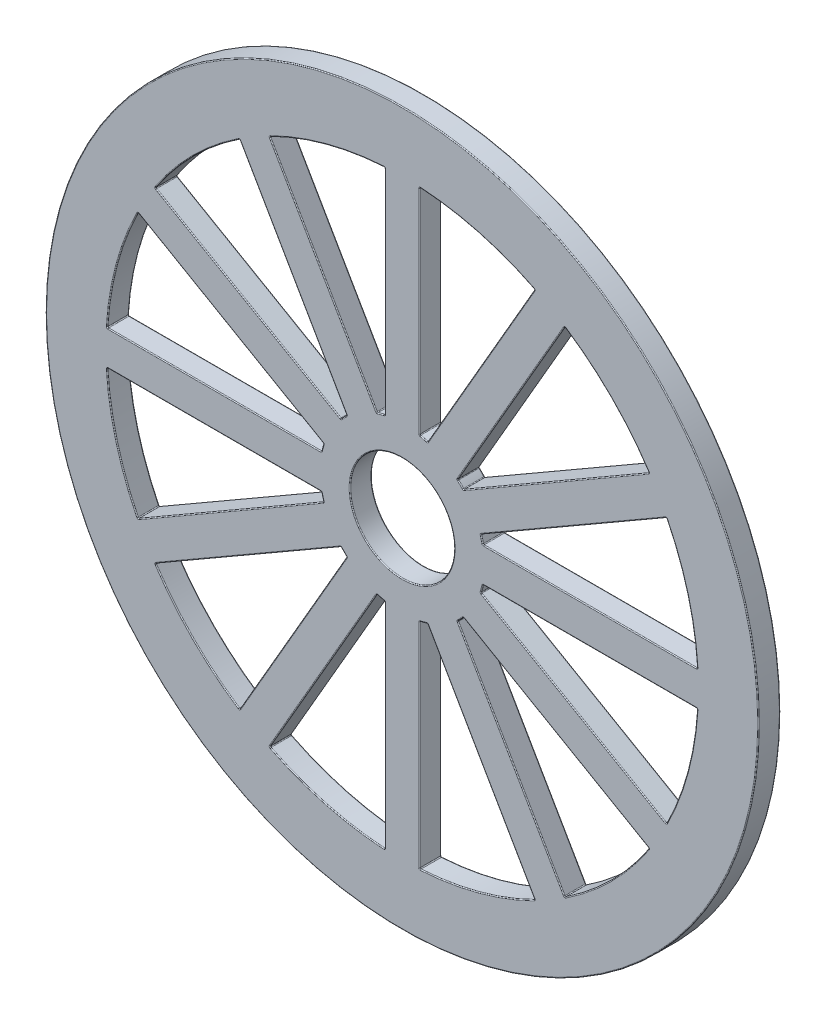
SolidWorks part; units mm, degrees
ref_plane "Plano frontal" through (0, 0, 0) normal (0, 0, 1) x (1, 0, 0)
ref_plane "Plano superior" through (0, 0, 0) normal (0, 1, 0) x (1, 0, 0)
ref_plane "Plano direito" through (0, 0, 0) normal (1, 0, 0) x (0, 0, -1)
sketch "Esboço1" plane through (0, 0, 0) normal (0, 0, 1) x (1, 0, 0)
  line L0 (-28.3848, 23.7524) -> (-28.3848, 48.4653)
  line L1 (-30.3848, 20.4653) -> (-30.3848, 48.4653) construction
  line L2 (-32.3848, 20.4653) -> (-32.3848, 48.4653) construction
  line L3 (-32.3848, 23.7524) -> (-32.3848, 48.4653)
  line L4 (-39.4276, 17.3768) -> (-60.8296, 29.7333)
  line L5 (-39.6718, 16.4653) -> (-64.3848, 16.4653)
  line L11 (-23.3419, 8.0897) -> (-1.9399, -4.2667)
  line L12 (-24.0092, 7.4224) -> (-11.6527, -13.9796)
  line L13 (-27.4733, 5.4224) -> (-15.1168, -15.9796)
  line L14 (-28.3848, 5.1782) -> (-28.3848, -19.5347)
  line L15 (-32.3848, 5.1782) -> (-32.3848, -19.5347)
  line L16 (-33.2963, 5.4224) -> (-45.6527, -15.9796)
  line L17 (-36.7604, 7.4224) -> (-49.1168, -13.9796)
  line L18 (-37.4276, 8.0897) -> (-58.8296, -4.2667)
  line L19 (-39.4276, 11.5538) -> (-60.8296, -0.8026)
  line L20 (-39.6718, 12.4653) -> (-64.3848, 12.4653)
  line L23 (-37.4276, 20.8409) -> (-58.8296, 33.1974)
  line L24 (-36.7604, 21.5082) -> (-49.1168, 42.9102)
  line L25 (-33.2963, 23.5082) -> (-45.6527, 44.9102)
  line L27 (-27.4733, 23.5082) -> (-15.1168, 44.9102)
  line L28 (-24.0092, 21.5082) -> (-11.6527, 42.9102)
  line L29 (-23.3419, 20.8409) -> (-1.9399, 33.1974)
  line L30 (-21.3419, 17.3768) -> (0.0601, 29.7333)
  line L31 (-21.0977, 16.4653) -> (3.6152, 16.4653)
  line L32 (-21.0977, 12.4653) -> (3.6152, 12.4653)
  line L33 (-21.3419, 11.5538) -> (0.0601, -0.8026)
  line L35 (-24.1886, 13.1974) -> (-22.9207, 12.4653) [skipped]
  line L37 (-24.3848, 16.4653) -> (-22.9207, 16.4653) [skipped]
  line L39 (-26.1886, 19.1974) -> (-24.9207, 19.9294) [skipped]
  line L40 (-29.1168, 20.6615) -> (-28.3848, 21.9294) [skipped]
  line L41 (-36.5809, 15.7333) -> (-37.8489, 16.4653) [skipped]
  circle A0 centre (-30.3848, 14.4653) radius 6
  circle A1 centre (-30.3848, 14.4653) radius 41
  circle A2 centre (-30.3848, 14.4653) radius 34
  circle A3 centre (-30.3848, 14.4653) radius 9.5
  point P57 (-30.3848, 14.4653)
  dimension "D1" = 12
  dimension "D2" = 68
  dimension "D3" = 82
  dimension "D4" = 19
  dimension "D6" = 2
  dimension "D7" = 12
extrude "Ressalto-extrusão1" add sketch "Esboço1" along normal blind 2.5
fillet "Filete1" radius 0.1 148 edges at (-21.0977, 16.4653, 1.25) (-21.3419, 17.3768, 1.25) (-1.9909, 33.1679, 1.25) (-23.3419, 20.8409, 1.25) (-15.1462, 44.8592, 1.25) (-27.4733, 23.5082, 1.25) (-32.3848, 48.4064, 1.25) (-32.3848, 23.7524, 1.25) (-49.0874, 42.8592, 1.25) (-36.7604, 21.5082, 1.25) (-60.7786, 29.7038, 1.25) (-39.4276, 17.3768, 1.25) (-64.3259, 12.4653, 1.25) (-39.6718, 12.4653, 1.25) (-58.7786, -4.2373, 1.25) (-37.4276, 8.0897, 1.25) (-45.6233, -15.9286, 1.25) (-33.2963, 5.4224, 1.25) (-28.3848, -19.4758, 1.25) (-28.3848, 5.1782, 1.25) (-11.6821, -13.9286, 1.25) (-24.0092, 7.4224, 1.25) (0.0091, -0.7732, 1.25) (-21.3419, 11.5538, 1.25) (0.0091, 29.7038, 1.25) (3.5564, 16.4653, 1.25) (-24.0092, 21.5082, 1.25) (-11.6821, 42.8592, 1.25) (-28.3848, 23.7524, 1.25) (-28.3848, 48.4064, 1.25) (-33.2963, 23.5082, 1.25) (-45.6233, 44.8592, 1.25) (-37.4276, 20.8409, 1.25) (-58.7786, 33.1679, 1.25) (-39.6718, 16.4653, 1.25) (-64.3259, 16.4653, 1.25) (-39.4276, 11.5538, 1.25) (-60.7786, -0.7732, 1.25) (-36.7604, 7.4224, 1.25) (-49.0874, -13.9286, 1.25) (-32.3848, 5.1782, 1.25) (-32.3848, -19.4758, 1.25) (-27.4733, 5.4224, 1.25) (-15.1462, -15.9286, 1.25) (-23.3419, 8.0897, 1.25) (-1.9909, -4.2373, 1.25) (-21.0977, 12.4653, 1.25) (3.5564, 12.4653, 1.25) (10.6152, 14.4653, 2.5) (10.6152, 14.4653, 0) (-24.3848, 14.4653, 2.5) (-24.3848, 14.4653, 0) (2.4567, 23.2652, 2.5) (2.4567, 23.2652, 0) (-10.6664, 23.5403, 0) (-10.6664, 23.5403, 2.5) (-21.2085, 16.9241, 2.5) (-21.2085, 16.9241, 0) (-8.7707, 16.4653, 0) (-8.7707, 16.4653, 2.5) (-17.8457, 32.1837, 0) (-17.8457, 32.1837, 2.5) (-23.6672, 21.1828, 2.5) (-23.6672, 21.1828, 0) (-12.6664, 27.0044, 0) (-12.6664, 27.0044, 2.5) (-6.3431, 38.5069, 2.5) (-6.3431, 38.5069, 0) (-28.3848, 36.0794, 0) (-28.3848, 36.0794, 2.5) (-27.926, 23.6416, 2.5) (-27.926, 23.6416, 0) (-21.3098, 34.1837, 0) (-21.3098, 34.1837, 2.5) (-21.5849, 47.3068, 2.5) (-21.5849, 47.3068, 0) (-39.4598, 34.1837, 0) (-39.4598, 34.1837, 2.5) (-32.8435, 23.6416, 2.5) (-32.8435, 23.6416, 0) (-32.3848, 36.0794, 0) (-32.3848, 36.0794, 2.5) (-39.1846, 47.3068, 2.5) (-39.1846, 47.3068, 0) (-48.1031, 27.0044, 0) (-48.1031, 27.0044, 2.5) (-37.1023, 21.1828, 2.5) (-37.1023, 21.1828, 0) (-42.9239, 32.1837, 0) (-42.9239, 32.1837, 2.5) (-54.4264, 38.5069, 2.5) (-54.4264, 38.5069, 0) (-51.9989, 16.4653, 0) (-51.9989, 16.4653, 2.5) (-39.5611, 16.9241, 2.5) (-39.5611, 16.9241, 0) (-50.1031, 23.5403, 0) (-50.1031, 23.5403, 2.5) (-63.2262, 23.2652, 2.5) (-63.2262, 23.2652, 0) (-50.1031, 5.3903, 0) (-50.1031, 5.3903, 2.5) (-39.5611, 12.0065, 2.5) (-39.5611, 12.0065, 0) (-51.9989, 12.4653, 0) (-51.9989, 12.4653, 2.5) (-63.2262, 5.6655, 2.5) (-63.2262, 5.6655, 0) (-42.9239, -3.2531, 0) (-42.9239, -3.2531, 2.5) (-37.1023, 7.7478, 2.5) (-37.1023, 7.7478, 0) (-48.1031, 1.9262, 0) (-48.1031, 1.9262, 2.5) (-54.4264, -9.5763, 2.5) (-54.4264, -9.5763, 0) (-32.3848, -7.1488, 0) (-32.3848, -7.1488, 2.5) (-32.8435, 5.289, 2.5) (-32.8435, 5.289, 0) (-39.4598, -5.2531, 0) (-39.4598, -5.2531, 2.5) (-39.1846, -18.3762, 2.5) (-39.1846, -18.3762, 0) (-21.3098, -5.2531, 0) (-21.3098, -5.2531, 2.5) (-27.926, 5.289, 2.5) (-27.926, 5.289, 0) (-28.3848, -7.1488, 0) (-28.3848, -7.1488, 2.5) (-21.5849, -18.3762, 2.5) (-21.5849, -18.3762, 0) (-12.6664, 1.9262, 0) (-12.6664, 1.9262, 2.5) (-23.6672, 7.7478, 2.5) (-23.6672, 7.7478, 0) (-17.8457, -3.2531, 0) (-17.8457, -3.2531, 2.5) (-6.3431, -9.5763, 2.5) (-6.3431, -9.5763, 0) (-8.7707, 12.4653, 0) (-8.7707, 12.4653, 2.5) (-21.2085, 12.0065, 2.5) (-21.2085, 12.0065, 0) (-10.6664, 5.3903, 0) (-10.6664, 5.3903, 2.5) (2.4567, 5.6655, 2.5) (2.4567, 5.6655, 0)
